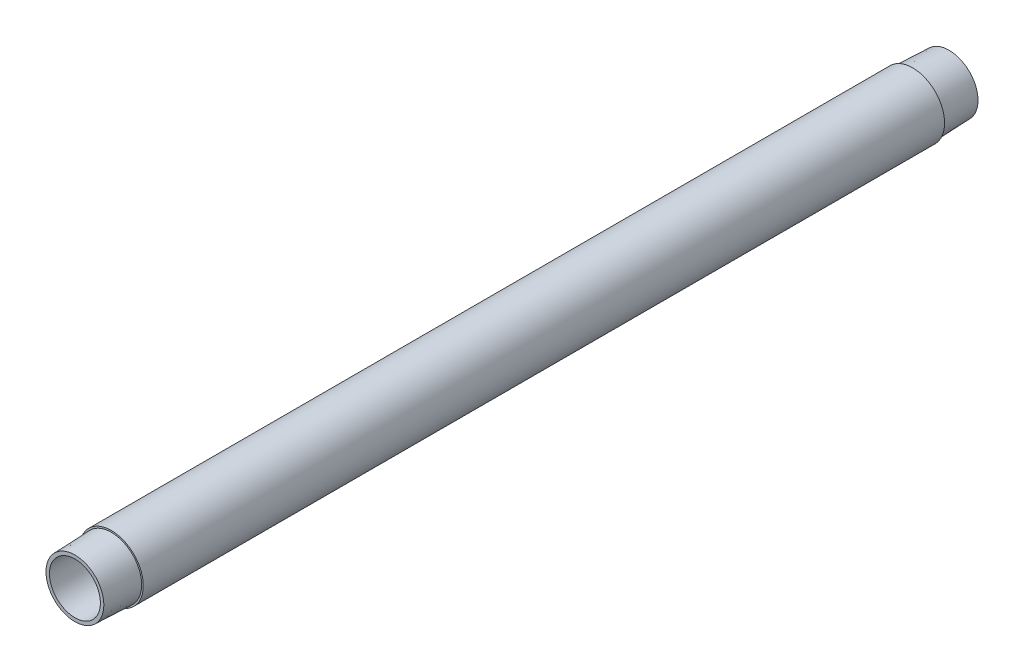
SolidWorks part; units mm, degrees
material "Plain Carbon Steel"
ref_plane "Front Plane" through (0, 0, 0) normal (0, 0, 1) x (1, 0, 0)
ref_plane "Top Plane" through (0, 0, 0) normal (0, 1, 0) x (1, 0, 0)
ref_plane "Right Plane" through (0, 0, 0) normal (1, 0, 0) x (0, 0, -1)
sketch "Sketch2" plane through (0, 0, 0) normal (0, 0, 1) x (1, 0, 0)
  circle A0 centre (0, 0) radius 13.3223
  circle A1 centre (0, 0) radius 16.7005
  dimension "D1" = 26.6446
  dimension "D2" = 33.401
extrude "Boss-Extrude1" add sketch "Sketch2" along normal blind 457.2
sketch "Sketch3" plane through (0, 0, 0) normal (1, 0, 0) x (0, 0, -1)
  line L0 (0, 21.8136) -> (-19.05, 21.8136)
  line L1 (-19.05, 21.8136) -> (-19.05, 16.7005)
  line L2 (0, 16.7005) -> (-457.2, 16.7005) construction
  line L3 (-19.05, 16.7005) -> (-19.05, 15.8693)
  line L4 (-19.05, 15.8693) -> (0, 15.1262)
  line L5 (0, -16.7005) -> (0, 16.7005) construction
  line L6 (0, 15.1262) -> (0, 21.8136)
  line L7 (-228.6, 16.7005) -> (-228.6, -16.7005) construction
  line L8 (-457.2, -16.7005) -> (0, -16.7005) construction
  line L9 (-457.2, 15.1262) -> (-457.2, 21.8136)
  line L10 (-438.15, 15.8693) -> (-457.2, 15.1262)
  line L11 (-438.15, 16.7005) -> (-438.15, 15.8693)
  line L12 (-438.15, 21.8136) -> (-438.15, 16.7005)
  line L13 (-457.2, 21.8136) -> (-438.15, 21.8136)
  line L14 (-228.6, 0) -> (-182.2331, 0) construction
  dimension "D1" = 19.05
  dimension "D2" = 19.05
revolve "Cut-Revolve2" cut sketch "Sketch3" angle 360 about L14
